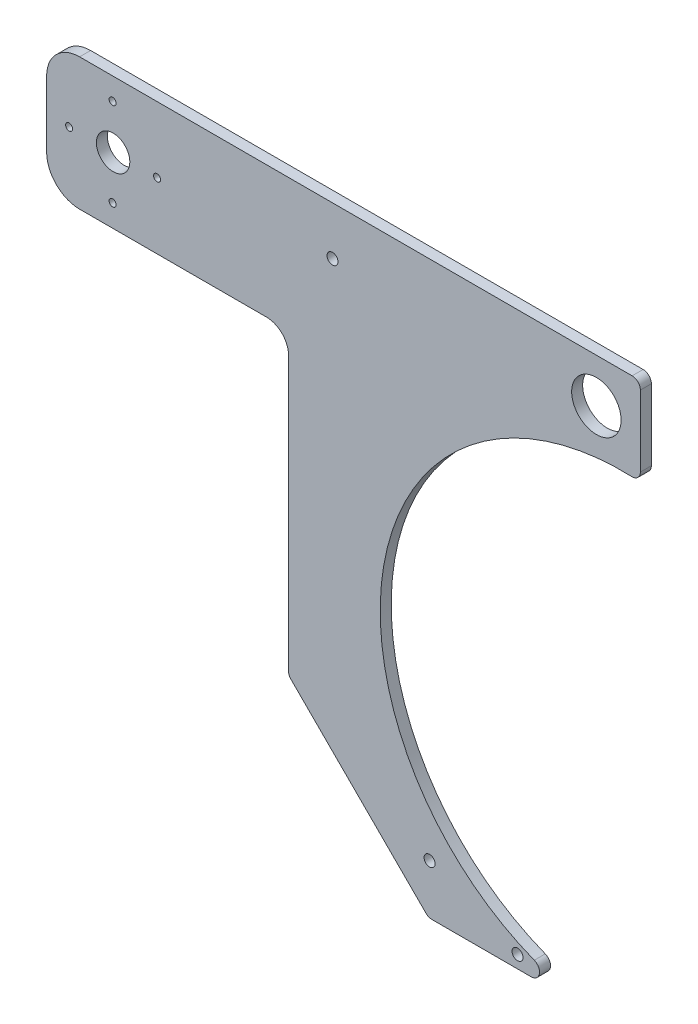
SolidWorks part; units mm, degrees
ref_plane "Front Plane" through (0, 0, 0) normal (0, 0, 1) x (1, 0, 0)
ref_plane "Top Plane" through (0, 0, 0) normal (0, 1, 0) x (1, 0, 0)
ref_plane "Right Plane" through (0, 0, 0) normal (1, 0, 0) x (0, 0, -1)
sketch "Sketch1" plane through (0, 0, 0) normal (0, 0, 1) x (1, 0, 0)
  line L0 (0, 1.9727) -> (0, 160.02)
  line L1 (4.7625, 248.92) -> (198.4375, 248.92)
  line L2 (203.2, 244.1575) -> (203.2, 203.1594)
  line L3 (1.3949, -1.3949) -> (79.4274, -79.4274)
  line L4 (82.795, -80.8223) -> (140.1943, -80.8223)
  line L5 (203.2, 248.92) -> (177.8, 248.92) construction
  line L6 (177.8, 248.92) -> (177.8, 223.52) construction
  line L7 (144.9568, -76.0598) -> (132.2568, -76.0598) construction
  line L8 (132.2568, -76.0598) -> (132.2568, -73.5198) construction
  line L9 (132.2568, -73.5198) -> (81.4568, -74.9287) construction
  line L10 (81.4568, -74.9287) -> (81.4568, -52.0687) construction
  line L11 (0, 248.92) -> (25.4, 248.92)
  line L12 (25.4, 248.92) -> (25.4, 220.98)
  line L14 (4.7625, 248.92) -> (0, 248.92)
  line L15 (0, 248.92) -> (-101.6, 248.92)
  line L17 (-101.6, 172.72) -> (-12.7, 172.72)
  line L18 (-101.6, 172.72) -> (-120.65, 172.72)
  line L19 (-139.7, 191.77) -> (-139.7, 229.87)
  line L20 (-120.65, 248.92) -> (-101.6, 248.92)
  line L21 (-120.65, 172.72) -> (-101.6, 172.72)
  line L22 (-120.65, 248.92) -> (-101.6, 248.92)
  arc A0 (141.927, -71.6237) -> (198.2522, 198.4005) centre (192.8112, 58.6488) cw
  arc A1 (0.8006, 246.8004) -> (4.7625, 248.92) centre (4.7625, 244.1575) cw
  arc A2 (203.2, 244.1575) -> (198.4375, 248.92) centre (198.4375, 244.1575) ccw
  arc A3 (198.2522, 198.4005) -> (203.2, 203.1594) centre (198.4375, 203.1594) ccw
  arc A4 (1.3949, -1.3949) -> (0, 1.9727) centre (4.7625, 1.9727) cw
  arc A5 (79.4274, -79.4274) -> (82.795, -80.8223) centre (82.795, -76.0598) ccw
  arc A6 (140.1943, -80.8223) -> (141.927, -71.6237) centre (140.1943, -76.0598) ccw
  circle A7 centre (177.8, 223.52) radius 14.2875
  circle A8 centre (132.2568, -73.5198) radius 3.175
  circle A9 centre (81.4568, -52.0687) radius 3.175
  circle A10 centre (25.4, 220.98) radius 3.175
  arc A11 (0, 160.02) -> (-12.7, 172.72) centre (-12.7, 160.02) ccw
  arc A12 (-120.65, 248.92) -> (-139.7, 229.87) centre (-120.65, 229.87) ccw
  arc A13 (-139.7, 191.77) -> (-120.65, 172.72) centre (-120.65, 191.77) ccw
  circle A14 centre (-101.3113, 210.8211) radius 9.652
  circle A15 centre (-75.9113, 210.8211) radius 2.032
  circle A16 centre (-126.7113, 210.8211) radius 2.032
  circle A17 centre (-101.6, 236.2211) radius 2.032
  circle A18 centre (-101.6, 185.4211) radius 2.032
  point P10 (0, 248.92)
  point P13 (203.2, 248.92)
  point P16 (203.2, 198.12)
  point P19 (0, 0)
  point P22 (80.8223, -80.8223)
  point P25 (182.4223, -80.8223)
  point P53 (-139.7, 172.72)
  point P63 (0, 0)
  point P64 (0, 0)
  point P67 (-93.5754, 213.3513)
  dimension "D7" = 4.7625
  dimension "D10" = 28.575
  dimension "D13" = 6.35
  dimension "D16" = 6.35
  dimension "D19" = 6.35
  dimension "D23" = 12.7
  dimension "D24" = 19.05
  dimension "D25" = 19.304
  dimension "D26" = 4.064
  dimension "D30" = 4.064
  dimension "D31" = 4.064
  dimension "D1" = 248.92
  dimension "D2" = 203.2
  dimension "D3" = 50.8
  dimension "D4" = 135
  dimension "D5" = 114.3
  dimension "D6" = 101.6
  dimension "D8" = 25.4
  dimension "D9" = 25.4
  dimension "D11" = 12.7
  dimension "D12" = 2.54
  dimension "D14" = 50.8
  dimension "D15" = 22.86
  dimension "D17" = 25.4
  dimension "D18" = 27.94
  dimension "D20" = 279.4
  dimension "D21" = 76.2
  dimension "D22" = 38.1
  dimension "D27" = 25.4
  dimension "D28" = 38.1
  dimension "D29" = 0
  dimension "D32" = 25.4
  dimension "D33" = 25.4
  dimension "D34" = 25.4
extrude "Boss-Extrude3" add sketch "Sketch1" along normal blind 6.35
